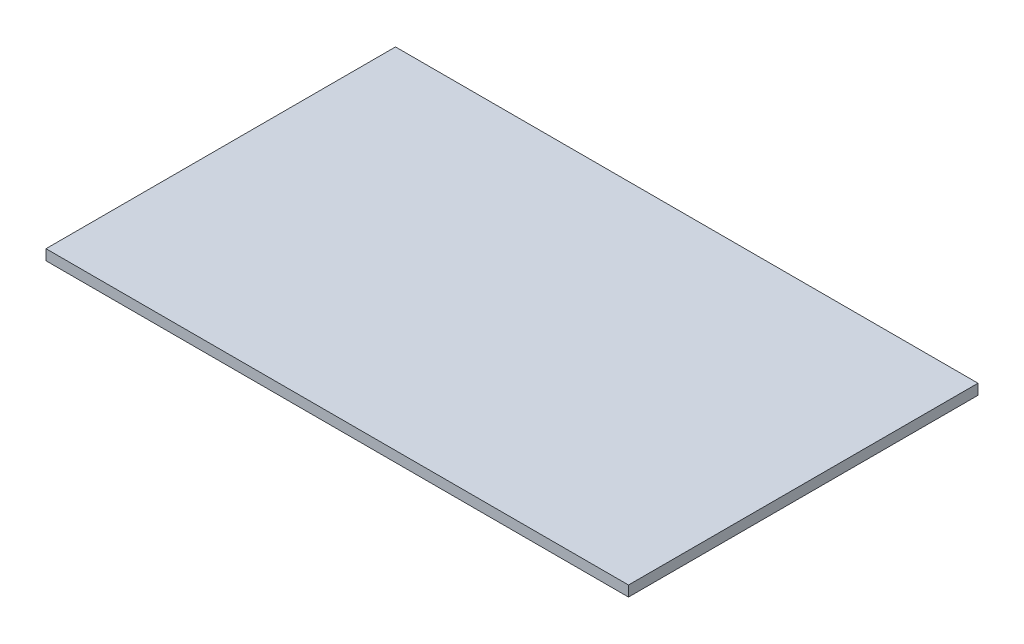
SolidWorks part; units mm, degrees
material "Quercia"
ref_plane "Piano frontale" through (0, 0, 0) normal (0, 0, 1) x (1, 0, 0)
ref_plane "Piano superiore" through (0, 0, 0) normal (0, 1, 0) x (1, 0, 0)
ref_plane "Piano destro" through (0, 0, 0) normal (1, 0, 0) x (0, 0, -1)
sketch "Schizzo1" plane through (0, 0, 0) normal (0, 1, 0) x (1, 0, 0)
  line L7 (-500, -300) -> (500, -300)
  line L8 (-500, -300) -> (-500, 300)
  line L9 (-500, 300) -> (500, 300)
  line L10 (500, -300) -> (500, 300)
  line L11 (-500, -300) -> (500, 300) construction
  line L12 (-500, 300) -> (500, -300) construction
  point P0 (0, 0)
  dimension "D1" = 1000
  dimension "D2" = 600
extrude "Estrusione-Estrusione1" add sketch "Schizzo1" along normal blind 18
